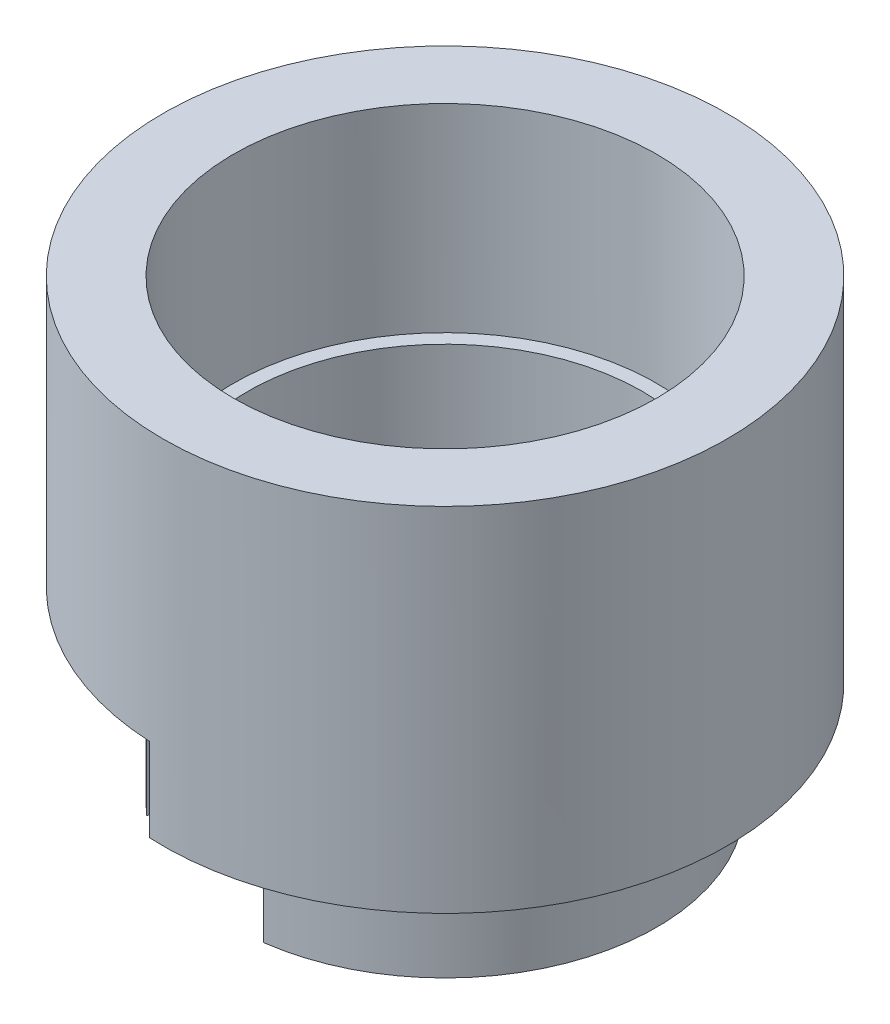
SolidWorks part; units mm, degrees
ref_plane "Plano frontal" through (0, 0, 0) normal (0, 0, 1) x (1, 0, 0)
ref_plane "Plano superior" through (0, 0, 0) normal (0, 1, 0) x (1, 0, 0)
ref_plane "Plano direito" through (0, 0, 0) normal (1, 0, 0) x (0, 0, -1)
sketch "Esboço1" plane through (0, 0, 0) normal (0, 1, 0) x (1, 0, 0)
  circle A0 centre (0, 0) radius 40
  circle A1 centre (0, 0) radius 30
extrude "Ressalto-extrusão1" add sketch "Esboço1" along normal blind 50
ref_plane "Plano1" through (0, 0, 0) normal (0, -1, 0) x (-1, 0, 0)
sketch "Esboço2" plane through (0, 0, 0) normal (0, -1, 0) x (-1, 0, 0)
  line L0 (0, 0) -> (0, -36) construction
  circle A0 centre (0, 0) radius 36 construction
  circle A2 centre (-21.1603, -29.1246) radius 1.5
  circle A3 centre (-34.238, -11.1246) radius 1.5
  circle A4 centre (-34.238, 11.1246) radius 1.5
  circle A7 centre (21.1603, 29.1246) radius 1.5
  circle A8 centre (34.238, 11.1246) radius 1.5
  circle A9 centre (34.238, -11.1246) radius 1.5
  point P25 (0, 0)
extrude "Corte-extrusão1" cut sketch "Esboço2" against normal blind 10
ref_plane "Plano2" through (0, 0, 0) normal (0, -1, 0) x (-1, 0, 0)
sketch "Esboço3" plane through (0, 0, 0) normal (0, -1, 0) x (-1, 0, 0)
  line L0 (16.0924, 28.8103) -> (19.5059, 34.9216)
  line L2 (1.4629, -29.9643) -> (1.9505, -39.9524)
  line L5 (-3.148, 29.8344) -> (-4.1974, 39.7792)
  line L6 (-3.148, 29.8344) -> (-6.3064, 59.7672) construction
  line L7 (30.2939, -13.0873) -> (36.1269, -17.1712)
  line L8 (36.1269, -17.1712) -> (30.2939, -13.0873) construction
  arc A1 (1.4629, -29.9643) -> (-3.148, 29.8344) centre (0, 0) ccw
  arc A2 (1.9505, -39.9524) -> (-4.1974, 39.7792) centre (0, 0) ccw
  arc A3 (30.2939, -13.0873) -> (16.0924, 28.8103) centre (0, 0) ccw
extrude "Corte-extrusão2" cut sketch "Esboço3" against normal blind 11.85 contours L7 A3 L0 A2 L5 A1 L2
ref_plane "Plano3" through (0, 11.85, 0) normal (0, -1, 0) x (-1, 0, 0)
sketch "Esboço4" plane through (0, 11.85, 0) normal (0, -1, 0) x (-1, 0, 0)
  line L0 (-4.0088, -29.7309) -> (-4.7004, -27.6027)
  line L1 (19.9092, -22.4415) -> (19.2303, -20.3518)
  line L2 (-4.0088, -29.7309) -> (-7.1104, -20.1852) construction
  line L3 (16.666, -12.4598) -> (19.9092, -22.4415) construction
  arc A0 (19.9092, -22.4415) -> (-4.0088, -29.7309) centre (0, 0) ccw
  arc A1 (19.2303, -20.3518) -> (-4.7004, -27.6027) centre (0, 0) ccw
extrude "Ressalto-extrusão2" add sketch "Esboço4" along normal blind 26.85 and the other way blind 10
ref_plane "Plano4" through (0, 11.85, 0) normal (0, -1, 0) x (-1, 0, 0)
scale "Escala1" scale about origin uniform scaling yes scale factor 0.681818
